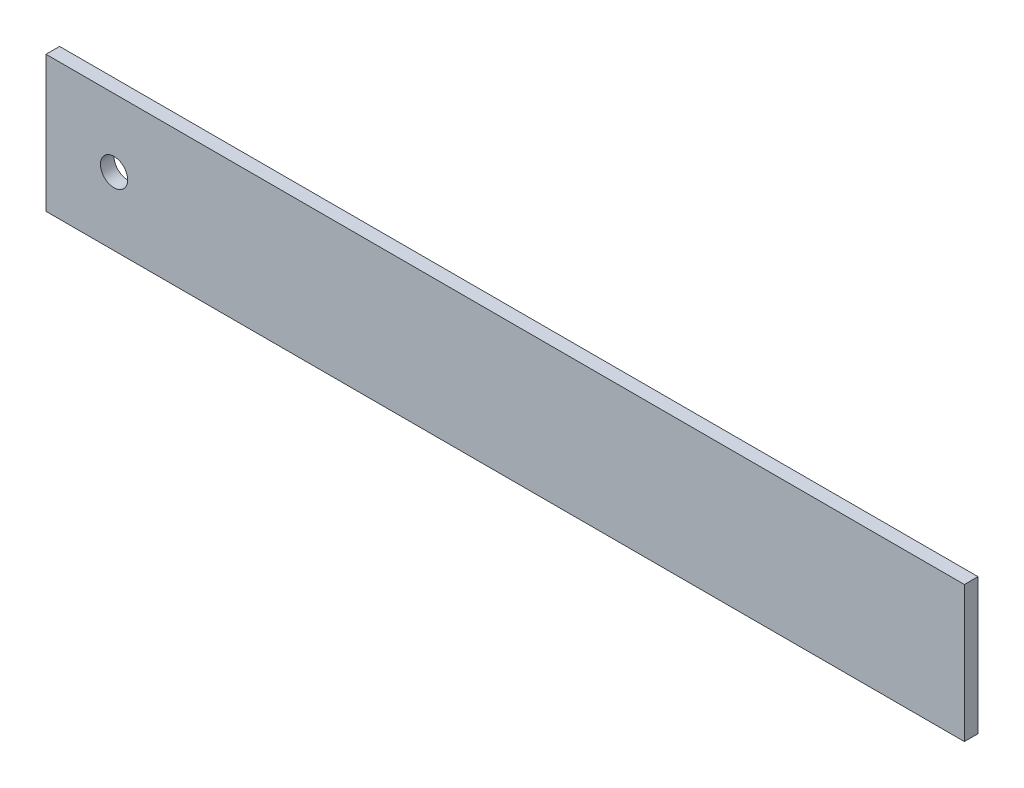
SolidWorks part; units mm, degrees
ref_plane "Front" through (0, 0, 0) normal (0, 0, 1) x (1, 0, 0)
ref_plane "Top" through (0, 0, 0) normal (0, 1, 0) x (1, 0, 0)
ref_plane "Right" through (0, 0, 0) normal (1, 0, 0) x (0, 0, -1)
sketch "Esquisse1" plane through (0, 0, 0) normal (0, 0, 1) x (1, 0, 0)
  line L1 (0, 0) -> (135, 0)
  line L2 (0, 0) -> (0, 20)
  line L3 (0, 20) -> (135, 20)
  line L4 (135, 0) -> (135, 20)
  dimension "D1" = 135
  dimension "D2" = 20
extrude "Boss.-Extru.1" add sketch "Esquisse1" along normal blind 2
sketch "Esquisse2" plane through (0, 0, 2) normal (0, 0, 1) x (1, 0, 0)
  line L0 (0, 10) -> (10, 10) construction
  line L1 (0, 20) -> (0, 0) construction
  circle A0 centre (10, 10) radius 2
  dimension "D1" = 4
  dimension "D2" = 10
extrude "Enlèv. mat.-Extru.1" cut sketch "Esquisse2" against normal through all
